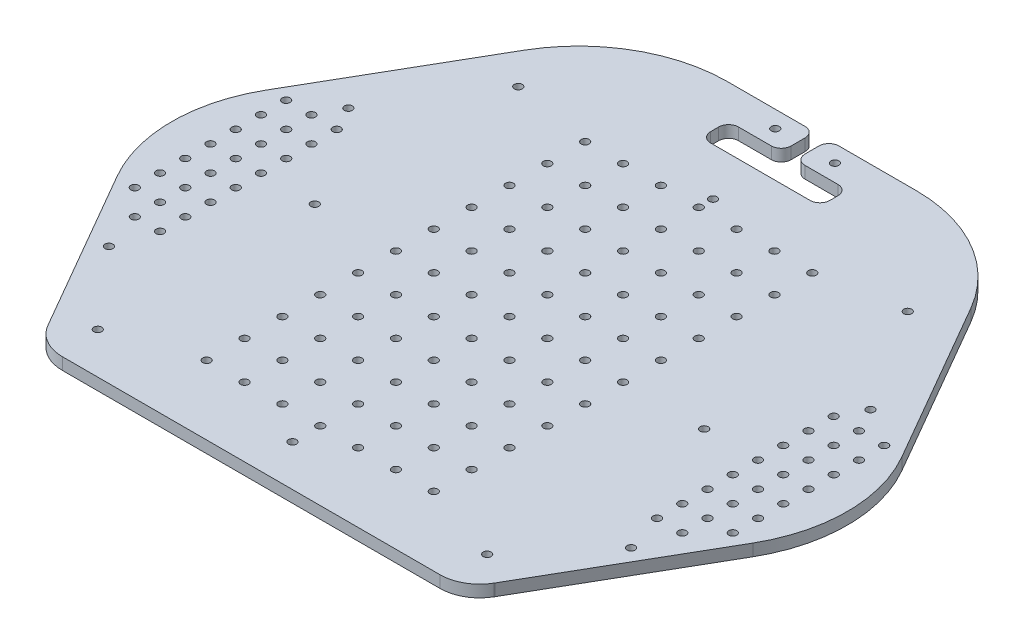
SolidWorks part; units mm, degrees
ref_plane "Plano frontal" through (0, 0, 0) normal (0, 0, 1) x (1, 0, 0)
ref_plane "Plano superior" through (0, 0, 0) normal (0, 1, 0) x (1, 0, 0)
ref_plane "Plano direito" through (0, 0, 0) normal (1, 0, 0) x (0, 0, -1)
ref_plane "Plano1" through (0, 6, 0) normal (0, 1, 0) x (1, 0, 0)
sketch "Esboço1" plane through (0, 6, 0) normal (0, 1, 0) x (1, 0, 0)
  line L0 (-94.9993, -130) -> (94.9993, -130)
  line L1 (112.4519, -119.7724) -> (159.9519, -37.5)
  line L2 (159.9519, 37.5) -> (112.4519, 119.7724)
  line L3 (47.5, 157.2724) -> (8.5, 157.2724)
  line L4 (3.5, 152.2724) -> (3.5, 145.2724)
  line L5 (8.5, 140.2724) -> (25, 140.2724)
  line L6 (30, 135.2724) -> (30, 131.2724)
  line L7 (25, 126.2724) -> (-25, 126.2724)
  line L8 (-30, 131.2724) -> (-30, 135.2724)
  line L9 (-25, 140.2724) -> (-8.5, 140.2724)
  line L10 (-3.5, 145.2724) -> (-3.5, 152.2724)
  line L11 (-8.5, 157.2724) -> (-47.5, 157.2724)
  line L12 (-112.4519, 119.7724) -> (-159.9519, 37.5)
  line L13 (-159.9519, -37.5) -> (-112.4519, -119.7724)
  circle A0 centre (150.5, -25.4) radius 2
  circle A1 centre (150.5, -12.7) radius 2
  circle A2 centre (150.5, 0) radius 2
  circle A3 centre (150.5, 12.7) radius 2
  circle A4 centre (150.5, 25.4) radius 2
  circle A5 centre (-150.5, -25.4) radius 2
  circle A6 centre (-150.5, -12.7) radius 2
  circle A7 centre (-150.5, 0) radius 2
  circle A8 centre (-150.5, 12.7) radius 2
  circle A9 centre (-150.5, 25.4) radius 2
  circle A10 centre (150.5, -38.1) radius 2
  circle A11 centre (150.5, 38.1) radius 2
  circle A12 centre (-150.5, -38.1) radius 2
  circle A13 centre (-150.5, 38.1) radius 2
  circle A14 centre (15, 148.77) radius 2
  circle A15 centre (-15, 148.77) radius 2
  circle A16 centre (131.4, -70.2) radius 2
  circle A17 centre (-131.4, -70.2) radius 2
  circle A18 centre (131.4, 50.3) radius 2
  circle A19 centre (-131.4, 50.3) radius 2
  circle A20 centre (98, -109.22) radius 2
  circle A21 centre (-125.0696, -50.8) radius 2
  circle A22 centre (-137.7696, -50.8) radius 2
  circle A23 centre (125.0696, -50.8) radius 2
  circle A24 centre (137.7696, -50.8) radius 2
  circle A25 centre (-137.7696, 12.7) radius 2
  circle A26 centre (-137.7696, 25.4) radius 2
  circle A27 centre (-137.7696, 38.1) radius 2
  circle A28 centre (-125.0696, 38.1) radius 2
  circle A29 centre (-125.0696, 25.4) radius 2
  circle A30 centre (-125.0696, 12.7) radius 2
  circle A31 centre (-137.7696, -12.7) radius 2
  circle A32 centre (-137.7696, -25.4) radius 2
  circle A33 centre (-137.7696, -38.1) radius 2
  circle A34 centre (-125.0696, -38.1) radius 2
  circle A35 centre (-125.0696, -25.4) radius 2
  circle A36 centre (-125.0696, -12.7) radius 2
  circle A37 centre (-137.7696, 0) radius 2
  circle A38 centre (-125.0696, 0) radius 2
  circle A39 centre (-97.9932, 0) radius 2
  circle A40 centre (137.7696, 12.7) radius 2
  circle A41 centre (137.7696, 25.4) radius 2
  circle A42 centre (137.7696, 38.1) radius 2
  circle A43 centre (125.0696, 38.1) radius 2
  circle A44 centre (125.0696, 25.4) radius 2
  circle A45 centre (125.0696, 12.7) radius 2
  circle A46 centre (137.7696, -12.7) radius 2
  circle A47 centre (137.7696, -25.4) radius 2
  circle A48 centre (137.7696, -38.1) radius 2
  circle A49 centre (125.0696, -38.1) radius 2
  circle A50 centre (125.0696, -25.4) radius 2
  circle A51 centre (125.0696, -12.7) radius 2
  circle A52 centre (137.7696, 0) radius 2
  circle A53 centre (125.0696, 0) radius 2
  circle A54 centre (97.9932, 0) radius 2
  circle A55 centre (57.15, -95.25) radius 2
  circle A56 centre (38.1, -95.25) radius 2
  circle A57 centre (19.05, -95.25) radius 2
  circle A58 centre (0, -95.25) radius 2
  circle A59 centre (-19.05, -95.25) radius 2
  circle A60 centre (-38.1, -95.25) radius 2
  circle A61 centre (-57.15, -95.25) radius 2
  circle A62 centre (-57.15, 95.25) radius 2
  circle A63 centre (-38.1, 95.25) radius 2
  circle A64 centre (-19.05, 95.25) radius 2
  circle A65 centre (0, 95.25) radius 2
  circle A66 centre (19.05, 95.25) radius 2
  circle A67 centre (38.1, 95.25) radius 2
  circle A68 centre (57.15, 95.25) radius 2
  circle A69 centre (57.15, -76.2) radius 2
  circle A70 centre (38.1, -76.2) radius 2
  circle A71 centre (19.05, -76.2) radius 2
  circle A72 centre (0, -76.2) radius 2
  circle A73 centre (-19.05, -76.2) radius 2
  circle A74 centre (-38.1, -76.2) radius 2
  circle A75 centre (-57.15, -76.2) radius 2
  circle A76 centre (-57.15, 76.2) radius 2
  circle A77 centre (-38.1, 76.2) radius 2
  circle A78 centre (-19.05, 76.2) radius 2
  circle A79 centre (0, 76.2) radius 2
  circle A80 centre (19.05, 76.2) radius 2
  circle A81 centre (38.1, 76.2) radius 2
  circle A82 centre (57.15, 76.2) radius 2
  circle A83 centre (57.15, -57.15) radius 2
  circle A84 centre (38.1, -57.15) radius 2
  circle A85 centre (19.05, -57.15) radius 2
  circle A86 centre (0, -57.15) radius 2
  circle A87 centre (-19.05, -57.15) radius 2
  circle A88 centre (-38.1, -57.15) radius 2
  circle A89 centre (-57.15, -57.15) radius 2
  circle A90 centre (-57.15, -38.1) radius 2
  circle A91 centre (-57.15, -19.05) radius 2
  circle A92 centre (-57.15, 0) radius 2
  circle A93 centre (-57.15, 19.05) radius 2
  circle A94 centre (-57.15, 38.1) radius 2
  circle A95 centre (-57.15, 57.15) radius 2
  circle A96 centre (-38.1, 57.15) radius 2
  circle A97 centre (-19.05, 57.15) radius 2
  circle A98 centre (0, 57.15) radius 2
  circle A99 centre (19.05, 57.15) radius 2
  circle A100 centre (38.1, 57.15) radius 2
  circle A101 centre (57.15, 57.15) radius 2
  circle A102 centre (57.15, 38.1) radius 2
  circle A103 centre (57.15, 19.05) radius 2
  circle A104 centre (57.15, 0) radius 2
  circle A105 centre (57.15, -19.05) radius 2
  circle A106 centre (57.15, -38.1) radius 2
  circle A107 centre (38.1, -38.1) radius 2
  circle A108 centre (19.05, -38.1) radius 2
  circle A109 centre (0, -38.1) radius 2
  circle A110 centre (-19.05, -38.1) radius 2
  circle A111 centre (-38.1, -38.1) radius 2
  circle A112 centre (-38.1, -19.05) radius 2
  circle A113 centre (-38.1, 0) radius 2
  circle A114 centre (-38.1, 19.05) radius 2
  circle A115 centre (-38.1, 38.1) radius 2
  circle A116 centre (-19.05, 38.1) radius 2
  circle A117 centre (0, 38.1) radius 2
  circle A118 centre (19.05, 38.1) radius 2
  circle A119 centre (38.1, 38.1) radius 2
  circle A120 centre (38.1, 19.05) radius 2
  circle A121 centre (38.1, 0) radius 2
  circle A122 centre (38.1, -19.05) radius 2
  circle A123 centre (19.05, -19.05) radius 2
  circle A124 centre (0, -19.05) radius 2
  circle A125 centre (-19.05, -19.05) radius 2
  circle A126 centre (-19.05, 0) radius 2
  circle A127 centre (-19.05, 19.05) radius 2
  circle A128 centre (0, 19.05) radius 2
  circle A129 centre (19.05, 19.05) radius 2
  circle A130 centre (19.05, 0) radius 2
  circle A131 centre (0, 0) radius 2
  circle A132 centre (0, -109.22) radius 2
  circle A133 centre (0, 102.4382) radius 2
  circle A134 centre (-98, 102.4382) radius 2
  circle A135 centre (98, 102.4382) radius 2
  circle A136 centre (-98, -109.22) radius 2
  arc A137 (-112.2717, -120.0828) -> (-94.9993, -130) centre (-94.9993, -110) ccw
  arc A138 (94.9993, -130) -> (112.2717, -120.0828) centre (94.9993, -110) ccw
  arc A139 (112.2717, -120.0828) -> (112.4519, -119.7724) centre (47.5, -82.2724) ccw
  arc A140 (159.9519, -37.5) -> (159.9519, 37.5) centre (95, 0) ccw
  arc A141 (112.4519, 119.7724) -> (47.5, 157.2724) centre (47.5, 82.2724) ccw
  arc A142 (8.5, 157.2724) -> (3.5, 152.2724) centre (8.5, 152.2724) ccw
  arc A143 (3.5, 145.2724) -> (8.5, 140.2724) centre (8.5, 145.2724) ccw
  arc A144 (25, 140.2724) -> (30, 135.2724) centre (25, 135.2724) cw
  arc A145 (30, 131.2724) -> (25, 126.2724) centre (25, 131.2724) cw
  arc A146 (-25, 126.2724) -> (-30, 131.2724) centre (-25, 131.2724) cw
  arc A147 (-30, 135.2724) -> (-25, 140.2724) centre (-25, 135.2724) cw
  arc A148 (-8.5, 140.2724) -> (-3.5, 145.2724) centre (-8.5, 145.2724) ccw
  arc A149 (-3.5, 152.2724) -> (-8.5, 157.2724) centre (-8.5, 152.2724) ccw
  arc A150 (-47.5, 157.2724) -> (-112.4519, 119.7724) centre (-47.5, 82.2724) ccw
  arc A151 (-159.9519, 37.5) -> (-159.9519, -37.5) centre (-95, 0) ccw
  arc A152 (-112.4519, -119.7724) -> (-112.2717, -120.0828) centre (-47.5, -82.2724) ccw
extrude "Ressalto-extrusão1" add sketch "Esboço1" against normal blind 6
